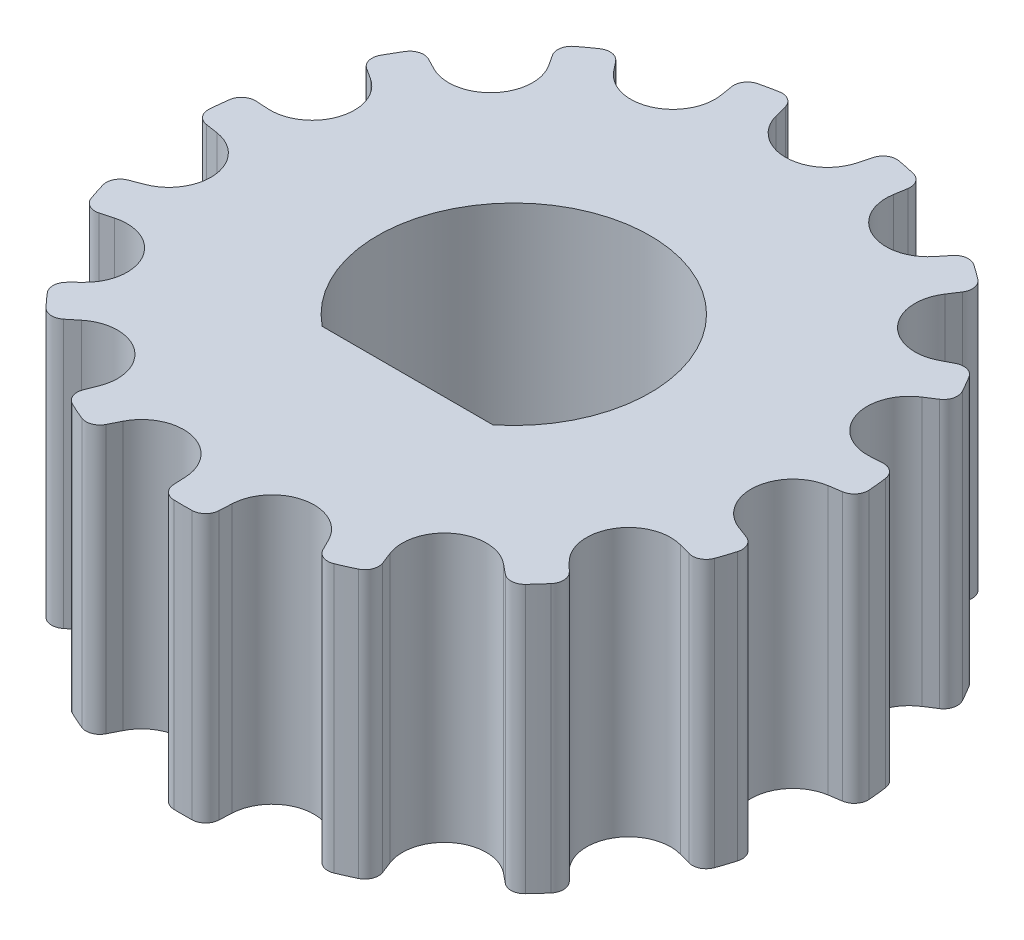
SolidWorks part; units mm, degrees
ref_plane "Front Plane" through (0, 0, 0) normal (0, 0, 1) x (1, 0, 0)
ref_plane "Top Plane" through (0, 0, 0) normal (0, 1, 0) x (1, 0, 0)
ref_plane "Right Plane" through (0, 0, 0) normal (1, 0, 0) x (0, 0, -1)
sketch "Sketch1" plane through (0, 0, 0) normal (0, 1, 0) x (1, 0, 0)
  circle A0 centre (0, 0) radius 7.162
  dimension "D1" = 14.3239
extrude "Boss-Extrude1" add sketch "Sketch1" along normal blind 5.8
sketch "Sketch2" plane through (0, 5.8, 0) normal (0, 1, 0) x (1, 0, 0)
  line L0 (0, 0) -> (0, 7.162) construction
  line L1 (-0.8799, 6.5598) -> (-0.95, 6.8255)
  line L2 (-2.913, 6.5428) -> (-2.913, 7.162)
  line L3 (-2.913, 7.162) -> (2.913, 7.162)
  line L4 (0.8799, 6.5598) -> (0.95, 6.8255)
  line L5 (2.913, 6.5428) -> (2.913, 7.162)
  circle A0 centre (0, 0) radius 7.162 construction
  arc A1 (0.8799, 6.5598) -> (-0.8799, 6.5598) centre (0, 6.792) cw
  arc A2 (-0.95, 6.8255) -> (-1.2943, 7.0441) centre (-1.2401, 6.749) ccw
  arc A4 (0.95, 6.8255) -> (1.2943, 7.0441) centre (1.2401, 6.749) cw
  arc A5 (-1.2943, 7.0441) -> (-2.913, 6.5428) centre (0, 0) ccw
  arc A6 (1.2943, 7.0441) -> (2.913, 6.5428) centre (0, 0) cw
  point P11 (0, 7.162)
  point P19 (0, 5.882)
  dimension "D3" = 0.3
  dimension "D5" = 0.91
  dimension "D2" = 0.95
  dimension "D4" = 1.28
  dimension "D6" = 24
extrude "Cut-Extrude1" cut sketch "Sketch2" against normal through all
pattern_circular "CirPattern1" count 15 over 360 about axis through (0, 0, 0) along (0, 1, 0) of "Cut-Extrude1"
sketch "Sketch3" plane through (0, 0, 0) normal (0, -1, 0) x (1, 0, 0)
  line L0 (1.8473, 2.3) -> (-1.8473, 2.3)
  arc A0 (-1.8473, 2.3) -> (1.8473, 2.3) centre (0, 0) ccw
  dimension "D1" = 5.9
  dimension "D2" = 2.3
extrude "Cut-Extrude2" cut sketch "Sketch3" against normal through all
sketch "Sketch5" plane through (0, 0, 0) normal (0, -1, 0) x (1, 0, 0)
  line L60 (5.4179, -3.8244) -> (5.6623, -3.9501)
  line L61 (6.252, -2.9286) -> (6.021, -2.7798)
  line L62 (6.505, -1.2901) -> (6.7794, -1.3055)
  line L63 (6.9027, -0.1325) -> (6.6311, -0.0906)
  line L64 (6.4674, 1.4673) -> (6.7243, 1.5648)
  line L65 (6.3598, 2.6865) -> (6.0946, 2.6144)
  line L66 (5.3115, 3.9709) -> (5.5065, 4.1645)
  line L67 (4.7173, 5.041) -> (4.5044, 4.8673)
  line L68 (3.2371, 5.788) -> (3.3366, 6.0442)
  line L69 (2.2591, 6.5239) -> (2.1352, 6.2786)
  line L70 (0.6031, 6.6042) -> (0.5897, 6.8787)
  line L71 (-0.5897, 6.8787) -> (-0.6031, 6.6042)
  line L72 (-2.1352, 6.2786) -> (-2.2591, 6.5239)
  line L73 (-3.3366, 6.0442) -> (-3.2371, 5.788)
  line L74 (-4.5044, 4.8673) -> (-4.7173, 5.041)
  line L75 (-5.5065, 4.1645) -> (-5.3115, 3.9709)
  line L76 (-6.0946, 2.6144) -> (-6.3598, 2.6865)
  line L77 (-6.7243, 1.5648) -> (-6.4674, 1.4673)
  line L78 (-6.6311, -0.0906) -> (-6.9027, -0.1325)
  line L79 (-6.7794, -1.3055) -> (-6.505, -1.2901)
  line L80 (-6.021, -2.7798) -> (-6.252, -2.9286)
  line L81 (-5.6623, -3.9501) -> (-5.4179, -3.8244)
  line L82 (-4.3698, -4.9885) -> (-4.5203, -5.2184)
  line L83 (-3.5661, -5.9117) -> (-3.394, -5.6974)
  line L84 (-1.963, -6.3345) -> (-2.007, -6.6058)
  line L85 (-0.8533, -6.851) -> (-0.7832, -6.5853)
  line L86 (0.7832, -6.5853) -> (0.8533, -6.851)
  line L87 (2.007, -6.6058) -> (1.963, -6.3345)
  line L88 (3.394, -5.6974) -> (3.5661, -5.9117)
  line L89 (4.5203, -5.2184) -> (4.3698, -4.9885)
  line L90 (5.4179, -3.8244) -> (5.6623, -3.9501)
  line L91 (6.252, -2.9286) -> (6.021, -2.7798)
  line L92 (6.505, -1.2901) -> (6.7794, -1.3055)
  line L93 (6.9027, -0.1325) -> (6.6311, -0.0906)
  line L94 (6.4674, 1.4673) -> (6.7243, 1.5648)
  line L95 (6.3598, 2.6865) -> (6.0946, 2.6144)
  line L96 (5.3115, 3.9709) -> (5.5065, 4.1645)
  line L97 (4.7173, 5.041) -> (4.5044, 4.8673)
  line L98 (3.2371, 5.788) -> (3.3366, 6.0442)
  line L99 (2.2591, 6.5239) -> (2.1352, 6.2786)
  line L100 (0.6031, 6.6042) -> (0.5897, 6.8787)
  line L101 (-0.5897, 6.8787) -> (-0.6031, 6.6042)
  line L102 (-2.1352, 6.2786) -> (-2.2591, 6.5239)
  line L103 (-3.3366, 6.0442) -> (-3.2371, 5.788)
  line L104 (-4.5044, 4.8673) -> (-4.7173, 5.041)
  line L105 (-5.5065, 4.1645) -> (-5.3115, 3.9709)
  line L106 (-6.0946, 2.6144) -> (-6.3598, 2.6865)
  line L107 (-6.7243, 1.5648) -> (-6.4674, 1.4673)
  line L108 (-6.6311, -0.0906) -> (-6.9027, -0.1325)
  line L109 (-6.7794, -1.3055) -> (-6.505, -1.2901)
  line L110 (-6.021, -2.7798) -> (-6.252, -2.9286)
  line L111 (-5.6623, -3.9501) -> (-5.4179, -3.8244)
  line L112 (-4.3698, -4.9885) -> (-4.5203, -5.2184)
  line L113 (-3.5661, -5.9117) -> (-3.394, -5.6974)
  line L114 (-1.963, -6.3345) -> (-2.007, -6.6058)
  line L115 (-0.8533, -6.851) -> (-0.7832, -6.5853)
  line L116 (0.7832, -6.5853) -> (0.8533, -6.851)
  line L117 (2.007, -6.6058) -> (1.963, -6.3345)
  line L118 (3.394, -5.6974) -> (3.5661, -5.9117)
  line L119 (4.5203, -5.2184) -> (4.3698, -4.9885)
  circle A60 centre (0, 0) radius 3.9038
  arc A120 (5.6623, -3.9501) -> (6.186, -3.8039) centre (5.8452, -3.5944) ccw
  arc A121 (6.186, -3.8039) -> (6.3873, -3.4553) centre (0, 0) ccw
  arc A122 (6.3873, -3.4553) -> (6.252, -2.9286) centre (6.0355, -3.2649) ccw
  arc A123 (6.505, -1.2901) -> (6.021, -2.7798) centre (6.4595, -2.0988) ccw
  arc A124 (6.7794, -1.3055) -> (7.1984, -0.959) centre (6.8019, -0.9062) ccw
  arc A125 (7.1984, -0.959) -> (7.2405, -0.5586) centre (0, 0) ccw
  arc A126 (7.2405, -0.5586) -> (6.9027, -0.1325) centre (6.8416, -0.5278) ccw
  arc A127 (6.4674, 1.4673) -> (6.6311, -0.0906) centre (6.7548, 0.71) ccw
  arc A128 (6.7243, 1.5648) -> (6.9661, 2.0518) centre (6.5824, 1.9387) ccw
  arc A129 (6.9661, 2.0518) -> (6.8417, 2.4347) centre (0, 0) ccw
  arc A130 (6.8417, 2.4347) -> (6.3598, 2.6865) centre (6.4648, 2.3006) ccw
  arc A131 (5.3115, 3.9709) -> (6.0946, 2.6144) centre (5.882, 3.396) ccw
  arc A132 (5.5065, 4.1645) -> (5.5293, 4.7077) centre (5.2248, 4.4484) ccw
  arc A133 (5.5293, 4.7077) -> (5.2599, 5.0069) centre (0, 0) ccw
  arc A134 (5.2599, 5.0069) -> (4.7173, 5.041) centre (4.9702, 4.7312) ccw
  arc A135 (3.2371, 5.788) -> (4.5044, 4.8673) centre (3.9922, 5.4948) ccw
  arc A136 (3.3366, 6.0442) -> (3.1365, 6.5497) centre (2.9637, 6.1889) ccw
  arc A137 (3.1365, 6.5497) -> (2.7687, 6.7135) centre (0, 0) ccw
  arc A138 (2.7687, 6.7135) -> (2.2591, 6.5239) centre (2.6162, 6.3437) ccw
  arc A139 (0.6031, 6.6042) -> (2.1352, 6.2786) centre (1.4121, 6.6436) ccw
  arc A140 (0.5897, 6.8787) -> (0.2013, 7.2592) centre (0.1902, 6.8593) ccw
  arc A141 (0.2013, 7.2592) -> (-0.2013, 7.2592) centre (0, 0) ccw
  arc A142 (-0.2013, 7.2592) -> (-0.5897, 6.8787) centre (-0.1902, 6.8593) ccw
  arc A143 (-2.1352, 6.2786) -> (-0.6031, 6.6042) centre (-1.4121, 6.6436) ccw
  arc A144 (-2.2591, 6.5239) -> (-2.7687, 6.7135) centre (-2.6162, 6.3437) ccw
  arc A145 (-2.7687, 6.7135) -> (-3.1365, 6.5497) centre (0, 0) ccw
  arc A146 (-3.1365, 6.5497) -> (-3.3366, 6.0442) centre (-2.9637, 6.1889) ccw
  arc A147 (-4.5044, 4.8673) -> (-3.2371, 5.788) centre (-3.9922, 5.4948) ccw
  arc A148 (-4.7173, 5.041) -> (-5.2599, 5.0069) centre (-4.9702, 4.7312) ccw
  arc A149 (-5.2599, 5.0069) -> (-5.5293, 4.7077) centre (0, 0) ccw
  arc A150 (-5.5293, 4.7077) -> (-5.5065, 4.1645) centre (-5.2248, 4.4484) ccw
  arc A151 (-6.0946, 2.6144) -> (-5.3115, 3.9709) centre (-5.882, 3.396) ccw
  arc A152 (-6.3598, 2.6865) -> (-6.8417, 2.4347) centre (-6.4648, 2.3006) ccw
  arc A153 (-6.8417, 2.4347) -> (-6.9661, 2.0518) centre (0, 0) ccw
  arc A154 (-6.9661, 2.0518) -> (-6.7243, 1.5648) centre (-6.5824, 1.9387) ccw
  arc A155 (-6.6311, -0.0906) -> (-6.4674, 1.4673) centre (-6.7548, 0.71) ccw
  arc A156 (-6.9027, -0.1325) -> (-7.2405, -0.5586) centre (-6.8416, -0.5278) ccw
  arc A157 (-7.2405, -0.5586) -> (-7.1984, -0.959) centre (0, 0) ccw
  arc A158 (-7.1984, -0.959) -> (-6.7794, -1.3055) centre (-6.8019, -0.9062) ccw
  arc A159 (-6.021, -2.7798) -> (-6.505, -1.2901) centre (-6.4595, -2.0988) ccw
  arc A160 (-6.252, -2.9286) -> (-6.3873, -3.4553) centre (-6.0355, -3.2649) ccw
  arc A161 (-6.3873, -3.4553) -> (-6.186, -3.8039) centre (0, 0) ccw
  arc A162 (-6.186, -3.8039) -> (-5.6623, -3.9501) centre (-5.8452, -3.5944) ccw
  arc A163 (-4.3698, -4.9885) -> (-5.4179, -3.8244) centre (-5.0474, -4.5447) ccw
  arc A164 (-4.5203, -5.2184) -> (-4.4297, -5.7545) centre (-4.1857, -5.4375) ccw
  arc A165 (-4.4297, -5.7545) -> (-4.104, -5.9911) centre (0, 0) ccw
  arc A166 (-4.104, -5.9911) -> (-3.5661, -5.9117) centre (-3.8779, -5.6611) ccw
  arc A167 (-1.963, -6.3345) -> (-3.394, -5.6974) centre (-2.7625, -6.2048) ccw
  arc A168 (-2.007, -6.6058) -> (-1.7062, -7.0587) centre (-1.6122, -6.6699) ccw
  arc A169 (-1.7062, -7.0587) -> (-1.3124, -7.1424) centre (0, 0) ccw
  arc A170 (-1.3124, -7.1424) -> (-0.8533, -6.851) centre (-1.2401, -6.749) ccw
  arc A171 (0.7832, -6.5853) -> (-0.7832, -6.5853) centre (0, -6.792) ccw
  arc A172 (0.8533, -6.851) -> (1.3124, -7.1424) centre (1.2401, -6.749) ccw
  arc A173 (1.3124, -7.1424) -> (1.7062, -7.0587) centre (0, 0) ccw
  arc A174 (1.7062, -7.0587) -> (2.007, -6.6058) centre (1.6122, -6.6699) ccw
  arc A175 (3.394, -5.6974) -> (1.963, -6.3345) centre (2.7625, -6.2048) ccw
  arc A176 (3.5661, -5.9117) -> (4.104, -5.9911) centre (3.8779, -5.6611) ccw
  arc A177 (4.104, -5.9911) -> (4.4297, -5.7545) centre (0, 0) ccw
  arc A178 (4.4297, -5.7545) -> (4.5203, -5.2184) centre (4.1857, -5.4375) ccw
  arc A179 (5.4179, -3.8244) -> (4.3698, -4.9885) centre (5.0474, -4.5447) ccw
  arc A180 (5.6623, -3.9501) -> (6.186, -3.8039) centre (5.8452, -3.5944) ccw
  arc A181 (6.186, -3.8039) -> (6.3873, -3.4553) centre (0, 0) ccw
  arc A182 (6.3873, -3.4553) -> (6.252, -2.9286) centre (6.0355, -3.2649) ccw
  arc A183 (6.505, -1.2901) -> (6.021, -2.7798) centre (6.4595, -2.0988) ccw
  arc A184 (6.7794, -1.3055) -> (7.1984, -0.959) centre (6.8019, -0.9062) ccw
  arc A185 (7.1984, -0.959) -> (7.2405, -0.5586) centre (0, 0) ccw
  arc A186 (7.2405, -0.5586) -> (6.9027, -0.1325) centre (6.8416, -0.5278) ccw
  arc A187 (6.4674, 1.4673) -> (6.6311, -0.0906) centre (6.7548, 0.71) ccw
  arc A188 (6.7243, 1.5648) -> (6.9661, 2.0518) centre (6.5824, 1.9387) ccw
  arc A189 (6.9661, 2.0518) -> (6.8417, 2.4347) centre (0, 0) ccw
  arc A190 (6.8417, 2.4347) -> (6.3598, 2.6865) centre (6.4648, 2.3006) ccw
  arc A191 (5.3115, 3.9709) -> (6.0946, 2.6144) centre (5.882, 3.396) ccw
  arc A192 (5.5065, 4.1645) -> (5.5293, 4.7077) centre (5.2248, 4.4484) ccw
  arc A193 (5.5293, 4.7077) -> (5.2599, 5.0069) centre (0, 0) ccw
  arc A194 (5.2599, 5.0069) -> (4.7173, 5.041) centre (4.9702, 4.7312) ccw
  arc A195 (3.2371, 5.788) -> (4.5044, 4.8673) centre (3.9922, 5.4948) ccw
  arc A196 (3.3366, 6.0442) -> (3.1365, 6.5497) centre (2.9637, 6.1889) ccw
  arc A197 (3.1365, 6.5497) -> (2.7687, 6.7135) centre (0, 0) ccw
  arc A198 (2.7687, 6.7135) -> (2.2591, 6.5239) centre (2.6162, 6.3437) ccw
  arc A199 (0.6031, 6.6042) -> (2.1352, 6.2786) centre (1.4121, 6.6436) ccw
  arc A200 (0.5897, 6.8787) -> (0.2013, 7.2592) centre (0.1902, 6.8593) ccw
  arc A201 (0.2013, 7.2592) -> (-0.2013, 7.2592) centre (0, 0) ccw
  arc A202 (-0.2013, 7.2592) -> (-0.5897, 6.8787) centre (-0.1902, 6.8593) ccw
  arc A203 (-2.1352, 6.2786) -> (-0.6031, 6.6042) centre (-1.4121, 6.6436) ccw
  arc A204 (-2.2591, 6.5239) -> (-2.7687, 6.7135) centre (-2.6162, 6.3437) ccw
  arc A205 (-2.7687, 6.7135) -> (-3.1365, 6.5497) centre (0, 0) ccw
  arc A206 (-3.1365, 6.5497) -> (-3.3366, 6.0442) centre (-2.9637, 6.1889) ccw
  arc A207 (-4.5044, 4.8673) -> (-3.2371, 5.788) centre (-3.9922, 5.4948) ccw
  arc A208 (-4.7173, 5.041) -> (-5.2599, 5.0069) centre (-4.9702, 4.7312) ccw
  arc A209 (-5.2599, 5.0069) -> (-5.5293, 4.7077) centre (0, 0) ccw
  arc A210 (-5.5293, 4.7077) -> (-5.5065, 4.1645) centre (-5.2248, 4.4484) ccw
  arc A211 (-6.0946, 2.6144) -> (-5.3115, 3.9709) centre (-5.882, 3.396) ccw
  arc A212 (-6.3598, 2.6865) -> (-6.8417, 2.4347) centre (-6.4648, 2.3006) ccw
  arc A213 (-6.8417, 2.4347) -> (-6.9661, 2.0518) centre (0, 0) ccw
  arc A214 (-6.9661, 2.0518) -> (-6.7243, 1.5648) centre (-6.5824, 1.9387) ccw
  arc A215 (-6.6311, -0.0906) -> (-6.4674, 1.4673) centre (-6.7548, 0.71) ccw
  arc A216 (-6.9027, -0.1325) -> (-7.2405, -0.5586) centre (-6.8416, -0.5278) ccw
  arc A217 (-7.2405, -0.5586) -> (-7.1984, -0.959) centre (0, 0) ccw
  arc A218 (-7.1984, -0.959) -> (-6.7794, -1.3055) centre (-6.8019, -0.9062) ccw
  arc A219 (-6.021, -2.7798) -> (-6.505, -1.2901) centre (-6.4595, -2.0988) ccw
  arc A220 (-6.252, -2.9286) -> (-6.3873, -3.4553) centre (-6.0355, -3.2649) ccw
  arc A221 (-6.3873, -3.4553) -> (-6.186, -3.8039) centre (0, 0) ccw
  arc A222 (-6.186, -3.8039) -> (-5.6623, -3.9501) centre (-5.8452, -3.5944) ccw
  arc A223 (-4.3698, -4.9885) -> (-5.4179, -3.8244) centre (-5.0474, -4.5447) ccw
  arc A224 (-4.5203, -5.2184) -> (-4.4297, -5.7545) centre (-4.1857, -5.4375) ccw
  arc A225 (-4.4297, -5.7545) -> (-4.104, -5.9911) centre (0, 0) ccw
  arc A226 (-4.104, -5.9911) -> (-3.5661, -5.9117) centre (-3.8779, -5.6611) ccw
  arc A227 (-1.963, -6.3345) -> (-3.394, -5.6974) centre (-2.7625, -6.2048) ccw
  arc A228 (-2.007, -6.6058) -> (-1.7062, -7.0587) centre (-1.6122, -6.6699) ccw
  arc A229 (-1.7062, -7.0587) -> (-1.3124, -7.1424) centre (0, 0) ccw
  arc A230 (-1.3124, -7.1424) -> (-0.8533, -6.851) centre (-1.2401, -6.749) ccw
  arc A231 (0.7832, -6.5853) -> (-0.7832, -6.5853) centre (0, -6.792) ccw
  arc A232 (0.8533, -6.851) -> (1.3124, -7.1424) centre (1.2401, -6.749) ccw
  arc A233 (1.3124, -7.1424) -> (1.7062, -7.0587) centre (0, 0) ccw
  arc A234 (1.7062, -7.0587) -> (2.007, -6.6058) centre (1.6122, -6.6699) ccw
  arc A235 (3.394, -5.6974) -> (1.963, -6.3345) centre (2.7625, -6.2048) ccw
  arc A236 (3.5661, -5.9117) -> (4.104, -5.9911) centre (3.8779, -5.6611) ccw
  arc A237 (4.104, -5.9911) -> (4.4297, -5.7545) centre (0, 0) ccw
  arc A238 (4.4297, -5.7545) -> (4.5203, -5.2184) centre (4.1857, -5.4375) ccw
  arc A239 (5.4179, -3.8244) -> (4.3698, -4.9885) centre (5.0474, -4.5447) ccw
  dimension "D1" = 0.1
extrude "Boss-Extrude2" [suppressed] add sketch "Sketch5" against normal up to surface (5.8 mm away)
equation "\"smallPulleyTeeth\"= 15"
equation "\"largePulleyTeeth\"= 40"
equation "\"eighthThick\"= 2.9mm"
equation "\"D1@Sketch1\"=3*\"smallPulleyTeeth\"/pi"
equation "\"D1@Boss-Extrude1\" = \"eighthThick\" * 2"
equation "\"D6@Sketch2\"=360/\"smallPulleyTeeth\""
equation "\"quarterThick\"=5.9mm"
equation "\"D1@CirPattern1\"=\"smallPulleyTeeth\""
equation "\"sixteenthThick\"= 1.7mm"
equation "\"OD\"= 145mm"
equation "\"puckAngle\"= 60.5deg"
equation "\"puckDiam\"= 76.5mm"
equation "\"axlePress\"= 5.9mm"
equation "\"press\"= 0.2mm"
equation "\"wheelClear\"= 0.3mm"
equation "\"10-32clear\"= 4.5mm"
equation "\"6-32clear\"= 3.3mm"
equation "\"8-32clear\"= 4.0mm"
equation "\"wheelHeight\"= 24mm"
equation "\"D1@Sketch3\"=\"axlePress\""
